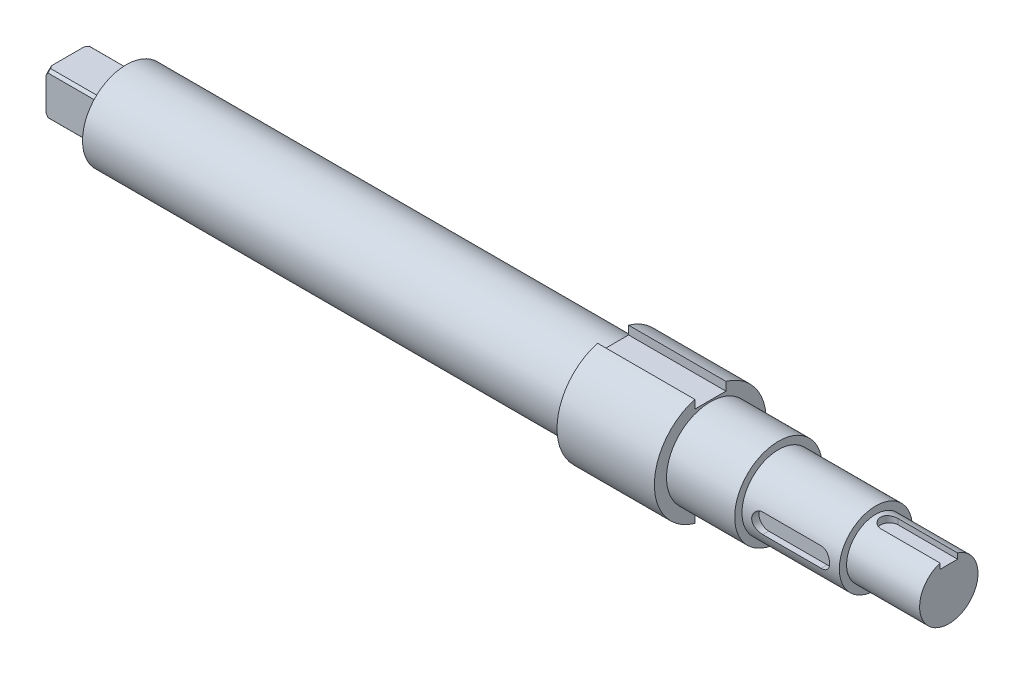
SolidWorks part; units mm, degrees
ref_plane "Front Plane" through (0, 0, 0) normal (0, 0, 1) x (1, 0, 0)
ref_plane "Top Plane" through (0, 0, 0) normal (0, 1, 0) x (1, 0, 0)
ref_plane "Right Plane" through (0, 0, 0) normal (1, 0, 0) x (0, 0, -1)
sketch "Sketch2" plane through (0, 0, 0) normal (1, 0, 0) x (0, 0, -1)
  circle A0 centre (0, 0) radius 11.5
  dimension "D1" = 23
extrude "Extrude1" add sketch "Sketch2" along normal blind 20
sketch "Sketch3" plane through (20, 0, 0) normal (1, 0, 0) x (0, 0, -1)
  circle A0 centre (0, 0) radius 9
  dimension "D1" = 18
extrude "Extrude2" add sketch "Sketch3" along normal blind 14
sketch "Sketch4" plane through (34, 0, 0) normal (1, 0, 0) x (0, 0, -1)
  circle A0 centre (0, 0) radius 7.5
  dimension "D1" = 15
extrude "Extrude3" add sketch "Sketch4" along normal blind 20
sketch "Sketch5" plane through (54, 0, 0) normal (1, 0, 0) x (0, 0, -1)
  circle A0 centre (0, 0) radius 6
  dimension "D1" = 12
extrude "Extrude4" add sketch "Sketch5" along normal blind 15
sketch "Sketch6" plane through (0, 0, 0) normal (-1, 0, 0) x (0, 0, 1)
  circle A0 centre (0, 0) radius 9
  dimension "D1" = 18
extrude "Extrude5" add sketch "Sketch6" along normal blind 100
sketch "Sketch7" plane through (-100, 0, 0) normal (-1, 0, 0) x (0, 0, 1)
  circle A0 centre (0, 0) radius 6
  dimension "D1" = 12
extrude "Extrude6" add sketch "Sketch7" along normal blind 12
scale "Scale1" scale about centroid uniform scaling yes scale factor 5
sketch "Sketch9" plane through (189.0137, 0, 0) normal (1, 0, 0) x (0, 0, -1)
  line L0 (-16, 46.5) -> (-16, 64.5)
  line L1 (-16, 46.5) -> (16, 46.5)
  line L2 (0, 46.5) -> (0, 64.5) construction
  line L3 (-16, 64.5) -> (16, 64.5)
  line L4 (16, 46.5) -> (16, 64.5)
  circle A0 centre (0, 0) radius 57.5 construction
  circle A1 centre (0, 0) radius 57.5 construction
  dimension "D3" = 11
  dimension "D1" = 32
  dimension "D2" = 18
extrude "Cut-Extrude1" cut sketch "Sketch9" against normal through all
mirror "Mirror1" about plane through (0, 0, 0) normal (0, 1, 0) of "Cut-Extrude1"
ref_plane "Plane1" through (0, 23, 0) normal (0, 1, 0) x (-1, 0, 0)
sketch "Sketch10" plane through (0, 23, 0) normal (0, 1, 0) x (-1, 0, 0)
  line L0 (-373.0137, -9) -> (-434.0137, -9)
  line L1 (-434.0137, 30) -> (-434.0137, -30) construction
  line L2 (-434.0137, -9) -> (-434.0137, 9)
  line L3 (-434.0137, 9) -> (-373.0137, 9)
  line L4 (-373.0137, 0) -> (-434.0137, 0) construction
  arc A0 (-373.0137, 9) -> (-373.0137, -9) centre (-373.0137, 0) cw
  dimension "D2" = 70
  dimension "D1" = 18
extrude "Cut-Extrude2" cut sketch "Sketch10" along normal through all
ref_plane "Plane2" through (0, 0, 30) normal (0, 0, 1) x (-1, 0, 0)
sketch "Sketch11" plane through (0, 0, 30) normal (0, 0, 1) x (-1, 0, 0)
  line L0 (-339.0137, 10) -> (-279.0137, 10)
  line L1 (-339.0137, -10) -> (-279.0137, -10)
  line L2 (-279.0137, 0) -> (-339.0137, 0) construction
  line L3 (-359.0137, 30) -> (-359.0137, -30) construction
  line L4 (-259.0137, 45) -> (-259.0137, -45) construction
  arc A0 (-279.0137, -10) -> (-279.0137, 10) centre (-279.0137, 0) ccw
  arc A1 (-339.0137, -10) -> (-339.0137, 10) centre (-339.0137, 0) cw
  dimension "D1" = 10
  dimension "D2" = 10
  dimension "D3" = 10
extrude "Cut-Extrude3" cut sketch "Sketch11" along normal through all
chamfer "Chamfer1" distance 2 angle 45 1 edges at (-470.9863, 0, 30)
sketch "Sketch12" plane through (-470.9863, 0, 0) normal (-1, 0, 0) x (0, 0, 1)
  line L0 (-22.5, -22.5) -> (-22.5, 22.5)
  line L1 (0, 0) -> (22.5, 0) construction
  line L2 (0, 0) -> (0, 22.5) construction
  line L3 (-22.5, 22.5) -> (22.5, 22.5)
  line L4 (22.5, -22.5) -> (22.5, 22.5)
  line L5 (-22.5, -22.5) -> (22.5, -22.5)
  line L6 (-40, -40) -> (-40, 40)
  line L7 (-40, -40) -> (40, -40)
  line L9 (-40, 40) -> (40, 40)
  line L10 (40, -40) -> (40, 40)
  point P8 (-22.5, 0)
  point P13 (0, 40)
  point P15 (-40, 0)
  point P16 (40, 0)
  dimension "D1" = 22.5
  dimension "D2" = 22.5
  dimension "D3" = 40
  dimension "D4" = 40
extrude "Cut-Extrude4" cut sketch "Sketch12" against normal blind 50
